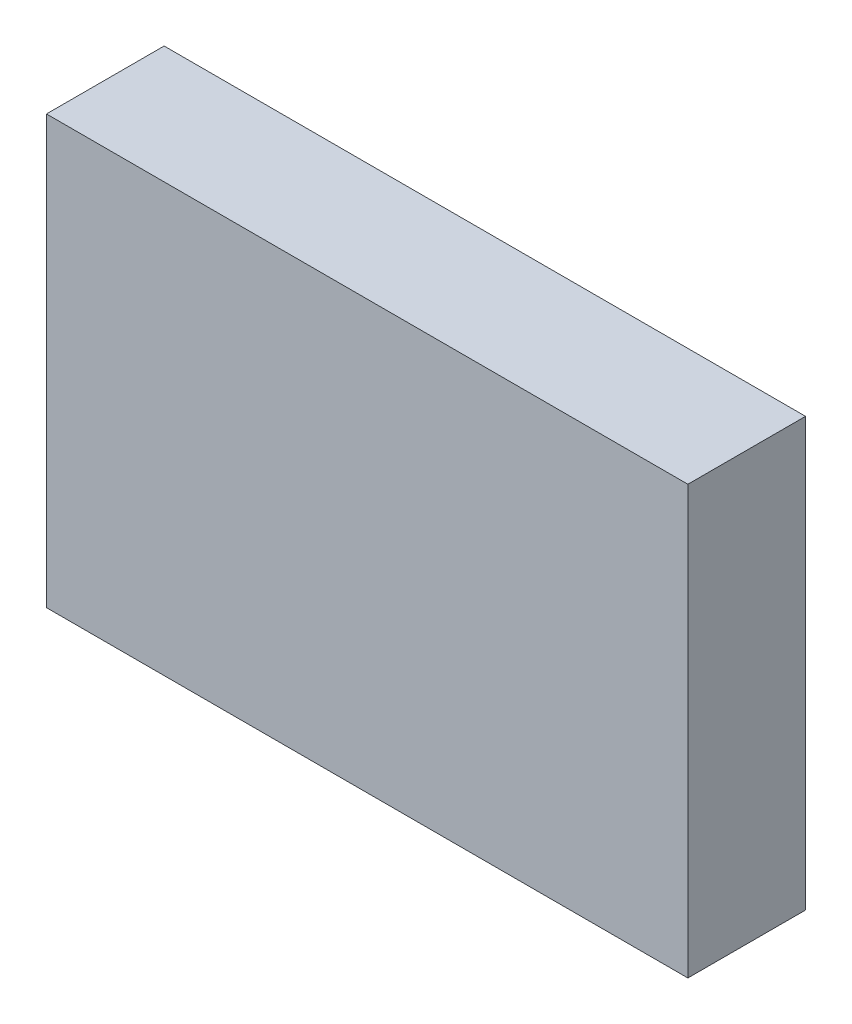
SolidWorks part; units mm, degrees
ref_plane "Front Plane" through (0, 0, 0) normal (0, 0, 1) x (1, 0, 0)
ref_plane "Top Plane" through (0, 0, 0) normal (0, 1, 0) x (1, 0, 0)
ref_plane "Right Plane" through (0, 0, 0) normal (1, 0, 0) x (0, 0, -1)
sketch "Sketch1" plane through (0, 0, 0) normal (0, 0, 1) x (1, 0, 0)
  line L1 (90, -60) -> (-90, -60)
  line L2 (90, -60) -> (90, 60)
  line L3 (90, 60) -> (-90, 60)
  line L4 (-90, -60) -> (-90, 60)
  line L5 (90, -60) -> (-90, 60) construction
  line L6 (90, 60) -> (-90, -60) construction
  point P0 (0, 0)
  dimension "D1" = 120
  dimension "D2" = 180
extrude "Boss-Extrude1" add sketch "Sketch1" along normal blind 33.02
